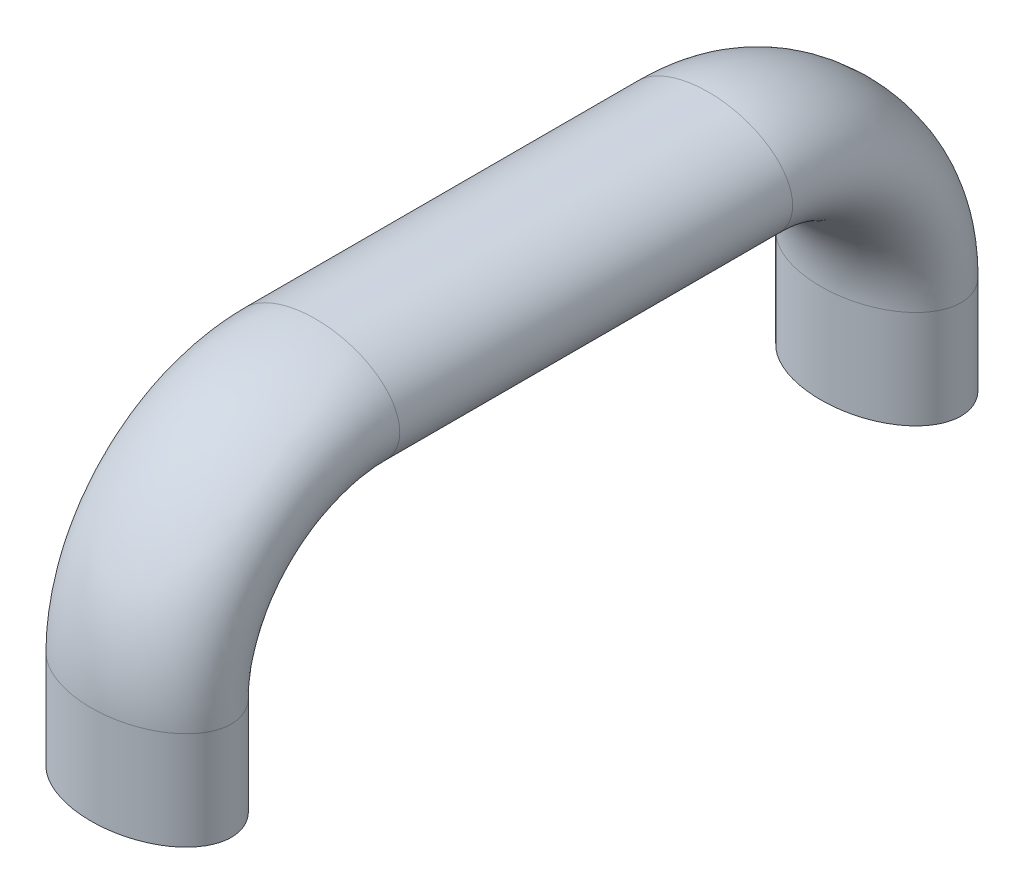
SolidWorks part; units mm, degrees
material "Caucho"
ref_plane "Alzado" through (0, 0, 0) normal (0, 0, 1) x (1, 0, 0)
ref_plane "Planta" through (0, 0, 0) normal (0, 1, 0) x (1, 0, 0)
ref_plane "Vista lateral" through (0, 0, 0) normal (1, 0, 0) x (0, 0, -1)
sketch "Croquis1" plane through (0, 0, 0) normal (0, 1, 0) x (1, 0, 0)
  ellipse E0 centre (0, 0) end of major axis (15, 0) minor radius 10
  dimension "D1" = 30
  dimension "D2" = 20
sketch "Croquis2" plane through (0, 0, 0) normal (1, 0, 0) x (0, 0, -1)
  line L1 (0, 0) -> (130, 0) construction
  line L2 (0, 0) -> (0, 17.5)
  line L3 (30, 47.5) -> (100, 47.5)
  line L4 (130, 0) -> (130, 17.5)
  arc A0 (100, 47.5) -> (130, 17.5) centre (100, 17.5) cw
  arc A1 (0, 17.5) -> (30, 47.5) centre (30, 17.5) cw
  point P7 (130, 47.5)
  point P10 (0, 47.5)
  dimension "D3" = 30
  dimension "D1" = 130
  dimension "D2" = 47.5
sweep "Barrer1" add profiles "Croquis1" path "Croquis2"
